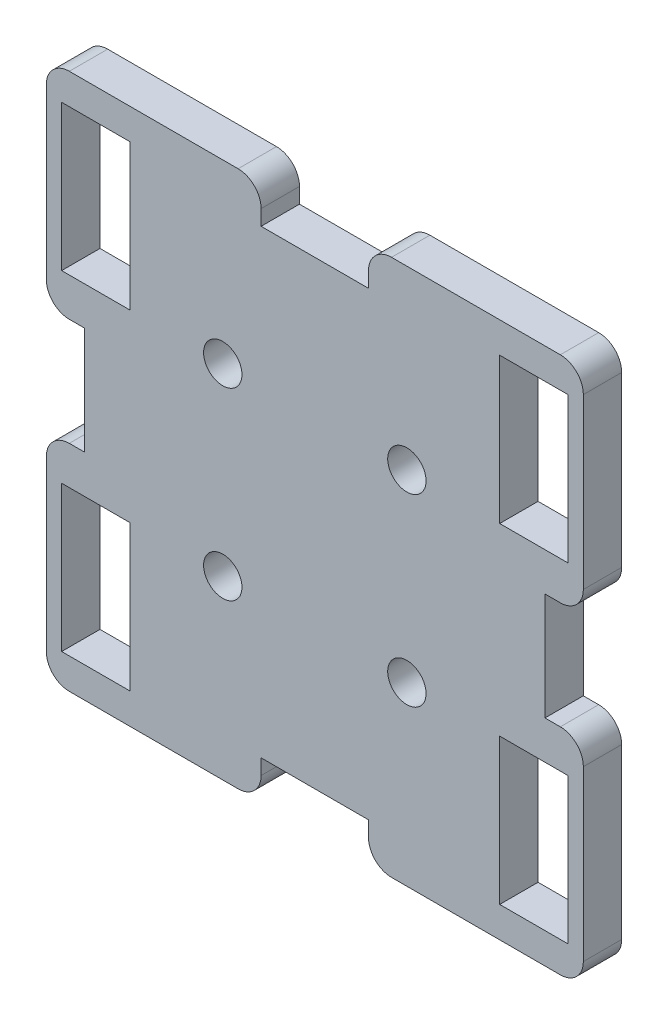
SolidWorks part; units mm, degrees
ref_plane "前视基准面" through (0, 0, 0) normal (0, 0, 1) x (1, 0, 0)
ref_plane "上视基准面" through (0, 0, 0) normal (0, 1, 0) x (1, 0, 0)
ref_plane "右视基准面" through (0, 0, 0) normal (1, 0, 0) x (0, 0, -1)
sketch "草图1" plane through (0, 0, 0) normal (0, 0, 1) x (1, 0, 0)
  line L0 (-18.8424, 47) -> (110.8246, 47) construction
  line L1 (3, 0) -> (25, 0)
  line L2 (0, 3) -> (0, 25)
  line L3 (3, 70) -> (25, 70)
  line L4 (70, 3) -> (70, 25)
  line L5 (125.9197, 23) -> (-17.1819, 23) construction
  line L6 (23, 80.3964) -> (23, 0) construction
  line L7 (47, 0) -> (47, 76.0189) construction
  line L8 (0, 70) -> (70, 0) construction
  line L9 (0, 0) -> (70, 70) construction
  line L10 (59.1, 66) -> (68, 66)
  line L11 (59.1, 23) -> (68, 23)
  line L12 (59.1, 23) -> (59.1, 4)
  line L13 (59.1, 4) -> (68, 4)
  line L14 (68, 23) -> (68, 4)
  line L15 (59.1, 66) -> (59.1, 47)
  line L16 (59.1, 47) -> (68, 47)
  line L17 (68, 66) -> (68, 47)
  line L18 (2, 66) -> (10.9, 66)
  line L19 (2, 66) -> (2, 47)
  line L20 (2, 47) -> (10.9, 47)
  line L21 (10.9, 66) -> (10.9, 47)
  line L22 (2, 23) -> (10.9, 23)
  line L23 (2, 23) -> (2, 4)
  line L24 (2, 4) -> (10.9, 4)
  line L25 (10.9, 23) -> (10.9, 4)
  line L26 (0, 45) -> (0, 67)
  line L28 (28, 67) -> (28, 65)
  line L29 (28, 65) -> (42, 65)
  line L30 (42, 67) -> (42, 65)
  line L33 (3, 42) -> (5, 42)
  line L34 (45, 0) -> (67, 0)
  line L35 (3, 28) -> (5, 28)
  line L36 (5, 42) -> (5, 28)
  line L37 (70, 45) -> (70, 67)
  line L39 (65, 42) -> (67, 42)
  line L40 (65, 42) -> (65, 28)
  line L41 (65, 28) -> (67, 28)
  line L42 (45, 70) -> (67, 70)
  line L46 (28, 3) -> (28, 5)
  line L47 (28, 5) -> (42, 5)
  line L48 (42, 3) -> (42, 5)
  circle A0 centre (23, 47) radius 2.5
  circle A1 centre (47, 47) radius 2.5
  circle A2 centre (23, 23) radius 2.5
  circle A3 centre (47, 23) radius 2.5
  circle A4 centre (23, 47) radius 9 construction
  circle A5 centre (47, 47) radius 9 construction
  circle A6 centre (47, 23) radius 9 construction
  circle A7 centre (23, 23) radius 9 construction
  arc A8 (28, 3) -> (25, 0) centre (25, 3) cw
  arc A9 (42, 3) -> (45, 0) centre (45, 3) ccw
  arc A10 (67, 0) -> (70, 3) centre (67, 3) ccw
  arc A11 (67, 28) -> (70, 25) centre (67, 25) cw
  arc A12 (67, 42) -> (70, 45) centre (67, 45) ccw
  arc A13 (67, 70) -> (70, 67) centre (67, 67) cw
  arc A14 (0, 67) -> (3, 70) centre (3, 67) cw
  arc A15 (3, 0) -> (0, 3) centre (3, 3) cw
  arc A16 (0, 25) -> (3, 28) centre (3, 25) cw
  arc A17 (0, 45) -> (3, 42) centre (3, 45) ccw
  arc A18 (45, 70) -> (42, 67) centre (45, 67) ccw
  arc A19 (25, 70) -> (28, 67) centre (25, 67) cw
  point P13 (35, 35)
  point P52 (42, 0)
  point P70 (70, 42)
  point P88 (6.45, 66)
  point P89 (63.55, 66)
  dimension "D7" = 19
  dimension "D15" = 2
  dimension "D19" = 3
  dimension "D1" = 70
  dimension "D2" = 70
  dimension "D3" = 24
  dimension "D4" = 24
  dimension "D5" = 12
  dimension "D6" = 12
  dimension "D8" = 8.9
  dimension "D9" = 19
  dimension "D10" = 8.9
  dimension "D11" = 19
  dimension "D12" = 8.9
  dimension "D13" = 19
  dimension "D14" = 8.9
  dimension "D16" = 2
  dimension "D17" = 2
  dimension "D18" = 2
  dimension "D20" = 57.1
  dimension "D25" = 14
extrude "凸台-拉伸1" add sketch "草图1" along normal blind 5
